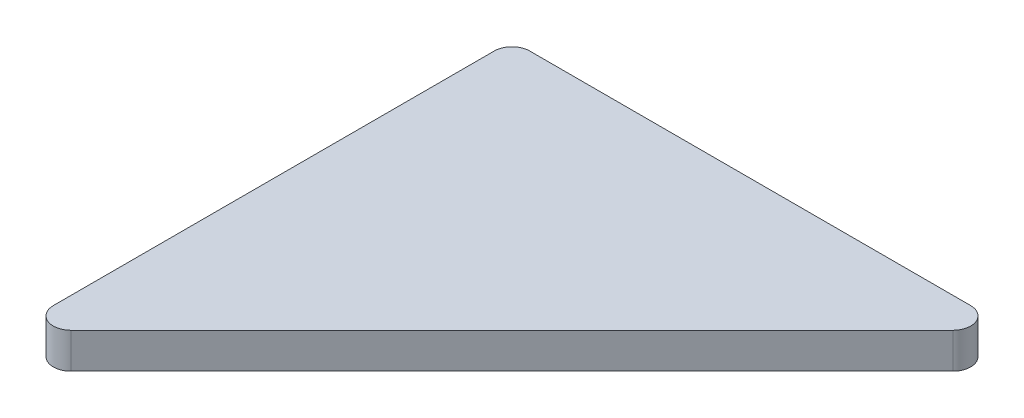
SolidWorks part; units mm, degrees
ref_plane "Front Plane" through (0, 0, 0) normal (0, 0, 1) x (1, 0, 0)
ref_plane "Top Plane" through (0, 0, 0) normal (0, 1, 0) x (1, 0, 0)
ref_plane "Right Plane" through (0, 0, 0) normal (1, 0, 0) x (0, 0, -1)
sketch "Sketch1" plane through (0, 0, 0) normal (0, 1, 0) x (1, 0, 0)
  line L0 (8.5355, -132.8858) -> (132.8858, -8.5355)
  line L1 (129.3503, 0) -> (5, 0)
  line L2 (0, -5) -> (0, -129.3503)
  line L3 (0, 0) -> (70.7107, -70.7107) construction
  arc A0 (5, 0) -> (0, -5) centre (5, -5) ccw
  arc A1 (132.8858, -8.5355) -> (129.3503, 0) centre (129.3503, -5) ccw
  arc A2 (8.5355, -132.8858) -> (0, -129.3503) centre (5, -129.3503) cw
  point P3 (70.7107, -70.7107)
  dimension "D2" = 5
  dimension "D1" = 100
extrude "Boss-Extrude1" add sketch "Sketch1" against normal blind 10
